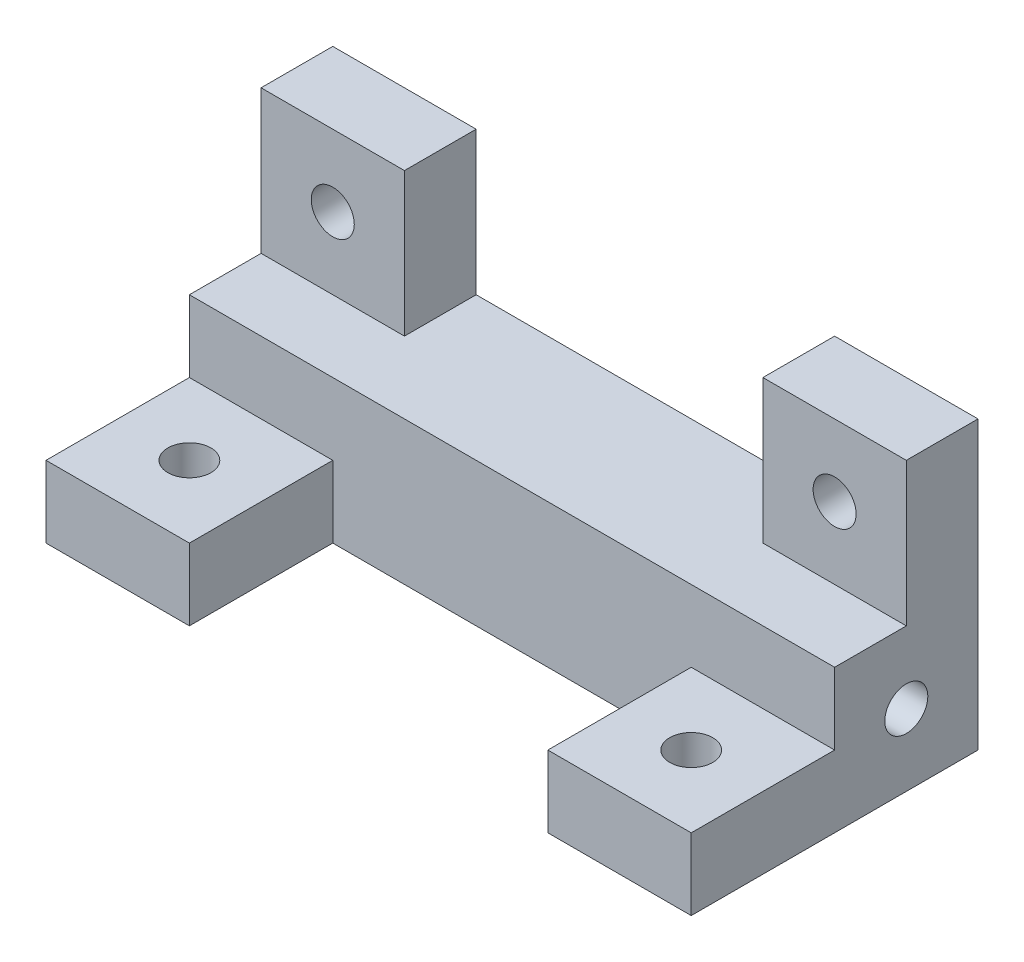
SolidWorks part; units mm, degrees
ref_plane "Front Plane" through (0, 0, 0) normal (0, 0, 1) x (1, 0, 0)
ref_plane "Top Plane" through (0, 0, 0) normal (0, 1, 0) x (1, 0, 0)
ref_plane "Right Plane" through (0, 0, 0) normal (1, 0, 0) x (0, 0, -1)
sketch "Sketch1" plane through (0, 0, 0) normal (0, 0, 1) x (1, 0, 0)
  line L1 (0, 0) -> (45, 0)
  line L2 (0, 0) -> (0, 10)
  line L3 (0, 10) -> (45, 10)
  line L4 (45, 0) -> (45, 10)
  dimension "D1" = 45
  dimension "D2" = 10
extrude "Boss-Extrude1" add sketch "Sketch1" along normal blind 10
sketch "Sketch2" plane through (0, 10, 0) normal (0, 1, 0) x (1, 0, 0)
  line L1 (0, 0) -> (10, 0)
  line L2 (0, 0) -> (0, -5)
  line L3 (0, -5) -> (10, -5)
  line L4 (10, 0) -> (10, -5)
  line L5 (45, 0) -> (35, 0)
  line L6 (45, 0) -> (45, -5)
  line L7 (45, -5) -> (35, -5)
  line L8 (35, 0) -> (35, -5)
  dimension "D1" = 5
  dimension "D2" = 5
  dimension "D3" = 10
  dimension "D4" = 10
extrude "Boss-Extrude2" add sketch "Sketch2" along normal blind 10
sketch "Sketch3" plane through (0, 0, 10) normal (0, 0, 1) x (1, 0, 0)
  line L1 (0, 0) -> (10, 0)
  line L2 (0, 0) -> (0, 5)
  line L3 (0, 5) -> (10, 5)
  line L4 (10, 0) -> (10, 5)
  line L5 (45, 0) -> (35, 0)
  line L6 (45, 0) -> (45, 5)
  line L7 (45, 5) -> (35, 5)
  line L8 (35, 0) -> (35, 5)
  dimension "D1" = 10
  dimension "D2" = 10
  dimension "D3" = 5
  dimension "D4" = 5
extrude "Boss-Extrude3" add sketch "Sketch3" along normal blind 10
sketch "Sketch4" plane through (0, 0, 0) normal (-1, 0, 0) x (0, 0, 1)
  line L0 (0, 20) -> (0, 0) construction
  line L1 (20, 0) -> (0, 0) construction
  circle A0 centre (5, 5) radius 1.5
  dimension "D3" = 3
  dimension "D1" = 5
  dimension "D2" = 5
extrude "Cut-Extrude1" cut sketch "Sketch4" against normal blind 5
sketch "Sketch5" plane through (0, 0, 5) normal (0, 0, 1) x (1, 0, 0)
  line L0 (0, 20) -> (10, 20) construction
  line L1 (10, 20) -> (10, 10) construction
  circle A0 centre (5, 15) radius 1.5
  dimension "D3" = 3
  dimension "D1" = 5
  dimension "D2" = 5
extrude "Cut-Extrude2" cut sketch "Sketch5" against normal blind 5
sketch "Sketch6" plane through (0, 5, 0) normal (0, 1, 0) x (1, 0, 0)
  line L0 (10, -20) -> (10, -10) construction
  line L1 (10, -20) -> (0, -20) construction
  circle A0 centre (5, -15) radius 1.5
  dimension "D3" = 3
  dimension "D1" = 5
  dimension "D2" = 5
extrude "Cut-Extrude3" cut sketch "Sketch6" against normal blind 5
sketch "Sketch7" plane through (45, 0, 0) normal (1, 0, 0) x (0, 0, -1)
  line L0 (0, 0) -> (0, 20) construction
  line L1 (-10, 10) -> (-5, 10) construction
  circle A0 centre (-5, 5) radius 1.5
  dimension "D3" = 3
  dimension "D1" = 5
  dimension "D2" = 5
extrude "Cut-Extrude4" cut sketch "Sketch7" against normal blind 5
sketch "Sketch8" plane through (0, 0, 5) normal (0, 0, 1) x (1, 0, 0)
  line L0 (45, 20) -> (45, 10) construction
  line L1 (35, 20) -> (45, 20) construction
  circle A0 centre (40, 15) radius 1.5
  point P4 (45, 15)
  dimension "D3" = 3
  dimension "D1" = 5
  dimension "D2" = 5
extrude "Cut-Extrude5" cut sketch "Sketch8" against normal blind 5 contours A0
sketch "Sketch9" plane through (0, 5, 0) normal (0, 1, 0) x (1, 0, 0)
  line L0 (45, -20) -> (45, -10) construction
  line L1 (45, -20) -> (35, -20) construction
  circle A0 centre (40, -15) radius 1.5
  dimension "D3" = 3
  dimension "D1" = 5
  dimension "D2" = 5
extrude "Cut-Extrude6" cut sketch "Sketch9" against normal blind 5
